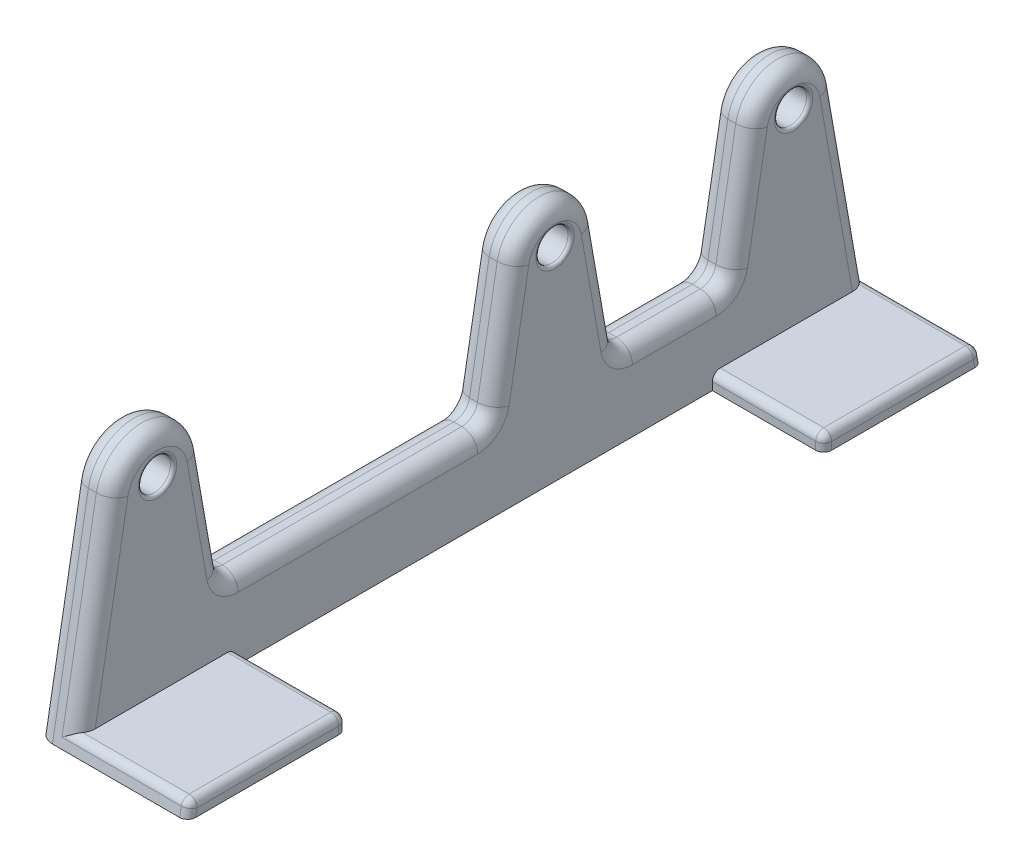
SolidWorks part; units mm, degrees
ref_plane "Front Plane" through (0, 0, 0) normal (0, 0, 1) x (1, 0, 0)
ref_plane "Top Plane" through (0, 0, 0) normal (0, 1, 0) x (1, 0, 0)
ref_plane "Right Plane" through (0, 0, 0) normal (1, 0, 0) x (0, 0, -1)
sketch "BaseSketch" plane through (0, 0, 0) normal (1, 0, 0) x (0, 0, -1)
  line L0 (0, 0) -> (500, 0)
  line L1 (55, 0) -> (-55, 0) construction
  line L2 (0, 0) -> (22.5743, 128.025)
  line L3 (22.5743, 128.025) -> (79.5288, 128.025) construction
  line L4 (79.5288, 128.025) -> (102.103, 0) construction
  line L5 (51.0515, 128.025) -> (51.0515, 0) construction
  line L6 (22.5743, 128.025) -> (51.0515, 123.0037) construction
  line L7 (51.0515, 123.0037) -> (79.5288, 128.025) construction
  line L8 (79.5288, 128.025) -> (93.4206, 49.2404)
  line L9 (424.6773, 128.025) -> (402.103, 0) construction
  line L10 (424.6773, 128.025) -> (477.4257, 128.025) construction
  line L11 (424.6773, 128.025) -> (410.7854, 49.2404)
  line L12 (451.0515, 128.025) -> (451.0515, 0) construction
  line L13 (424.6773, 128.025) -> (451.0515, 123.3745) construction
  line L14 (451.0515, 123.3745) -> (477.4257, 128.025) construction
  line L15 (477.4257, 128.025) -> (500, 0)
  line L16 (500, 0) -> (500, 49.2404) construction
  line L17 (500, 49.2404) -> (410.7854, 49.2404) construction
  line L18 (274.6773, 128.025) -> (252.103, 0) construction
  line L19 (274.6773, 128.025) -> (327.4257, 128.025) construction
  line L20 (274.6773, 128.025) -> (260.7854, 49.2404)
  line L21 (301.0515, 128.025) -> (301.0515, 0) construction
  line L22 (274.6773, 128.025) -> (301.0515, 123.3745) construction
  line L23 (301.0515, 123.3745) -> (327.4257, 128.025) construction
  line L25 (260.7854, 49.2404) -> (301.0515, 49.2404) construction
  line L26 (301.0515, 49.2404) -> (341.3176, 49.2404) construction
  line L27 (252.103, 0) -> (301.0515, 0) construction
  line L28 (301.0515, 0) -> (350, 0) construction
  line L29 (327.4257, 128.025) -> (350, 0) construction
  line L30 (93.4206, 49.2404) -> (260.7854, 49.2404)
  line L33 (341.3176, 49.2404) -> (327.4257, 128.025)
  line L34 (410.7854, 49.2404) -> (341.3176, 49.2404)
  arc A0 (79.5288, 128.025) -> (22.5743, 128.025) centre (51.0515, 123.0037) ccw
  arc A2 (477.4257, 128.025) -> (424.6773, 128.025) centre (451.0515, 123.3745) ccw
  arc A4 (327.4257, 128.025) -> (274.6773, 128.025) centre (301.0515, 123.3745) ccw
  dimension "D1" = 80
  dimension "D3" = 150
  dimension "D4" = 130
  dimension "D6" = 80
  dimension "D10" = 500
  dimension "D11" = 80
  dimension "D12" = 80
  dimension "D13" = 52.7484
  dimension "D14" = 80
  dimension "D15" = 26.7811
  dimension "D18" = 250
  dimension "D19" = 52.7484
  dimension "D20" = 80
  dimension "D21" = 26.7811
  dimension "D22" = 100
  dimension "D23" = 130
  dimension "D24" = 40.2661
  dimension "D25" = 80
extrude "BaseExtrude" add sketch "BaseSketch" against normal blind 25 contours L33 A4 L20 L30 L8 A0 L2 L0 L15 A2 L11 L34
sketch "Basewhlessketch" plane through (0, 0, 0) normal (1, 0, 0) x (0, 0, -1)
  line L0 (0, 0) -> (22.5743, 128.025) construction
  line L1 (22.5743, 128.025) -> (79.5288, 128.025) construction
  line L2 (79.5288, 128.025) -> (274.6773, 128.025) construction
  line L3 (274.6773, 128.025) -> (327.4257, 128.025) construction
  line L4 (327.4257, 128.025) -> (424.6773, 128.025) construction
  line L5 (424.6773, 128.025) -> (477.4257, 128.025) construction
  line L6 (451.0515, 128.025) -> (451.0515, 138.025) construction
  circle A0 centre (51.0515, 128.025) radius 10.1
  circle A1 centre (301.0515, 128.025) radius 10.1
  circle A2 centre (451.0515, 128.025) radius 10.1
  point P24 (301.0515, 128.025)
  point P27 (451.0515, 128.025)
  dimension "D1" = 20.2
  dimension "D2" = 20.2
  dimension "D3" = 20.2
extrude "WholesCut" cut sketch "Basewhlessketch" against normal blind 25
sketch "Sketch1" plane through (0, 0, 0) normal (1, 0, 0) x (0, 0, -1)
  line L0 (0, 0) -> (500, 0)
  line L1 (13.75, 0) -> (-13.75, 0) construction
  line L2 (477.4257, 128.025) -> (500, 0) construction
  line L3 (500, 0) -> (498.2635, 9.8481)
  line L5 (498.2635, 9.8481) -> (1.7365, 9.8481)
  line L6 (0, 0) -> (22.5743, 128.025) construction
  line L7 (1.7365, 9.8481) -> (0, 0)
extrude "Boss-Extrude1" add sketch "Sketch1" along normal blind 70 and the other way blind 10
sketch "Sketch2" plane through (70, 0, 0) normal (1, 0, 0) x (0, 0, -1)
  line L0 (0, 0) -> (100, 0) construction
  line L1 (13.75, 0) -> (-13.75, 0) construction
  line L2 (500, 0) -> (400, 0) construction
  line L3 (0, 0) -> (500, 0) construction
  line L4 (498.2635, 9.8481) -> (1.7365, 9.8481) construction
  line L5 (100, 0) -> (400, 0)
  line L6 (100, 0) -> (100, 9.8481)
  line L7 (100, 9.8481) -> (400, 9.8481)
  line L8 (400, 0) -> (400, 9.8481)
extrude "Cut-Extrude1" cut sketch "Sketch2" against normal blind 70
fillet "Fillet3" radius 10 26 edges at (-25, 64.0125, -488.7129) (0, 68.9365, -487.8446) (-25, 64.0125, -11.2871) (0, 68.9365, -12.1554) (-25, 150.1556, -451.0515) (0, 150.1556, -451.0515) (-25, 151.9203, -51.0515) (0, 151.9203, -51.0515) (-25, 150.1556, -301.0515) (0, 150.1556, -301.0515) (-25, 88.6327, -334.3717) (0, 88.6327, -334.3717) (-25, 88.6327, -417.7314) (0, 88.6327, -417.7314) (-25, 88.6327, -86.4747) (0, 88.6327, -86.4747) (-25, 88.6327, -267.7314) (0, 88.6327, -267.7314) (-12.5, 49.2404, -341.3176) (-25, 49.2404, -376.0515) (-12.5, 49.2404, -410.7854) (0, 49.2404, -376.0515) (-12.5, 49.2404, -93.4206) (-25, 49.2404, -177.103) (-12.5, 49.2404, -260.7854) (0, 49.2404, -177.103)
fillet "Fillet4" radius 5 10 edges at (70, 9.8481, -50.8682) (30, 9.8481, -1.7365) (35, 9.8481, -100) (70, 4.924, -0.8682) (70, 4.924, -100) (30, 9.8481, -498.2635) (70, 9.8481, -449.1318) (35, 9.8481, -400) (70, 4.924, -400) (70, 4.924, -499.1318)
fillet "Fillet5" radius 2 6 edges at (0, 128.025, -61.1515) (-25, 128.025, -61.1515) (0, 128.025, -461.1515) (-25, 128.025, -461.1515) (0, 128.025, -311.1515) (-25, 128.025, -311.1515)
scale "Scale1" scale about origin uniform scaling yes scale factor 0.5
